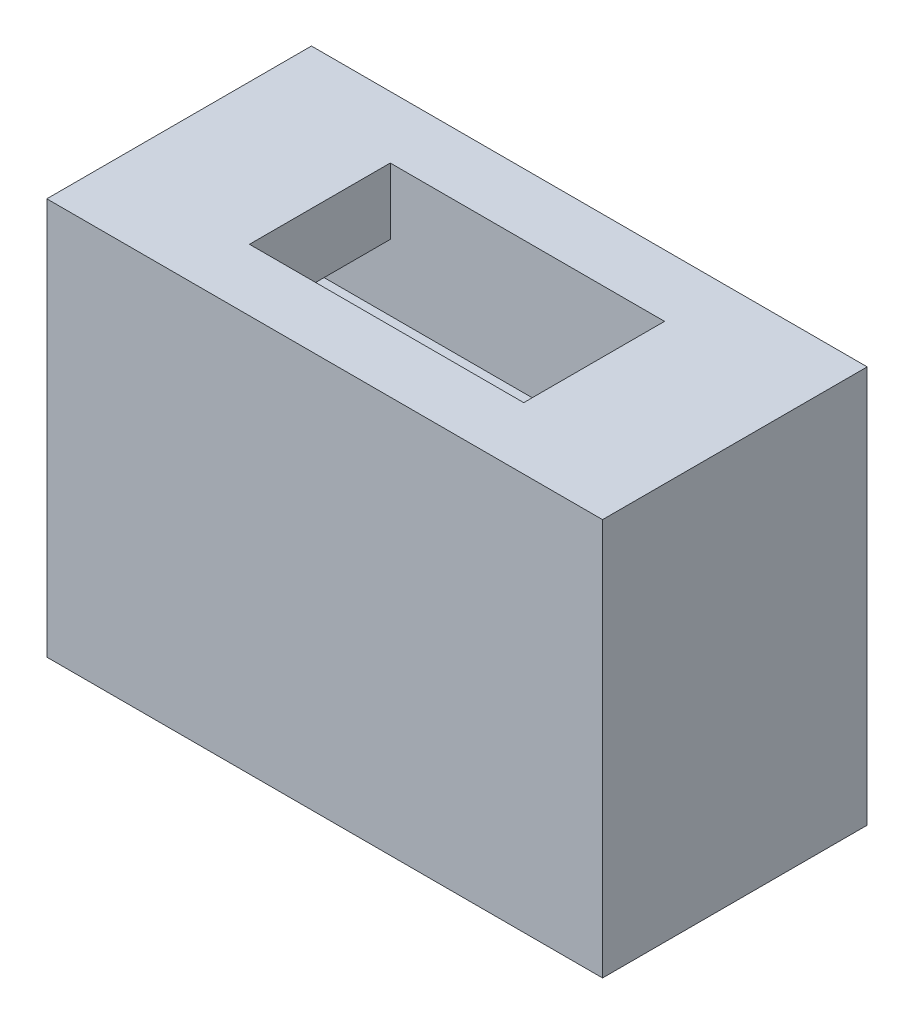
SolidWorks part; units mm, degrees
ref_plane "Plan de face" through (0, 0, 0) normal (0, 0, 1) x (1, 0, 0)
ref_plane "Plan de dessus" through (0, 0, 0) normal (0, 1, 0) x (1, 0, 0)
ref_plane "Plan de droite" through (0, 0, 0) normal (1, 0, 0) x (0, 0, -1)
sketch "Esquisse1" plane through (0, 0, 0) normal (0, 1, 0) x (1, 0, 0)
  line L1 (-21, 10) -> (21, 10)
  line L2 (-21, 10) -> (-21, -10)
  line L3 (-21, -10) -> (21, -10)
  line L4 (21, 10) -> (21, -10)
  line L5 (-21, 10) -> (21, -10) construction
  line L6 (-21, -10) -> (21, 10) construction
  point P0 (0, 0)
  dimension "D1" = 42
  dimension "D2" = 20
extrude "Boss.-Extru.1" add sketch "Esquisse1" along normal blind 30
sketch "Esquisse2" plane through (0, 30, 0) normal (0, 1, 0) x (1, 0, 0)
  line L1 (-10.3646, -5.3202) -> (10.3646, -5.3202)
  line L2 (-10.3646, -5.3202) -> (-10.3646, 5.3202)
  line L3 (-10.3646, 5.3202) -> (10.3646, 5.3202)
  line L4 (10.3646, -5.3202) -> (10.3646, 5.3202)
  line L5 (-10.3646, -5.3202) -> (10.3646, 5.3202) construction
  line L6 (-10.3646, 5.3202) -> (10.3646, -5.3202) construction
  point P0 (0, 0)
extrude "Enlèv. mat.-Extru.1" cut sketch "Esquisse2" against normal blind 10
sketch "Esquisse3" plane through (-10.3646, 0, 0) normal (1, 0, 0) x (0, 0, -1)
  line L0 (5.3202, 20) -> (5.3202, 30) construction
  line L1 (-5.3202, 20) -> (5.3202, 20)
  line L2 (-5.3202, 20) -> (-5.3202, 25)
  line L3 (-5.3202, 25) -> (5.3202, 25)
  line L4 (5.3202, 20) -> (5.3202, 25)
extrude "Enlèv. mat.-Extru.2" cut sketch "Esquisse3" against normal through all
